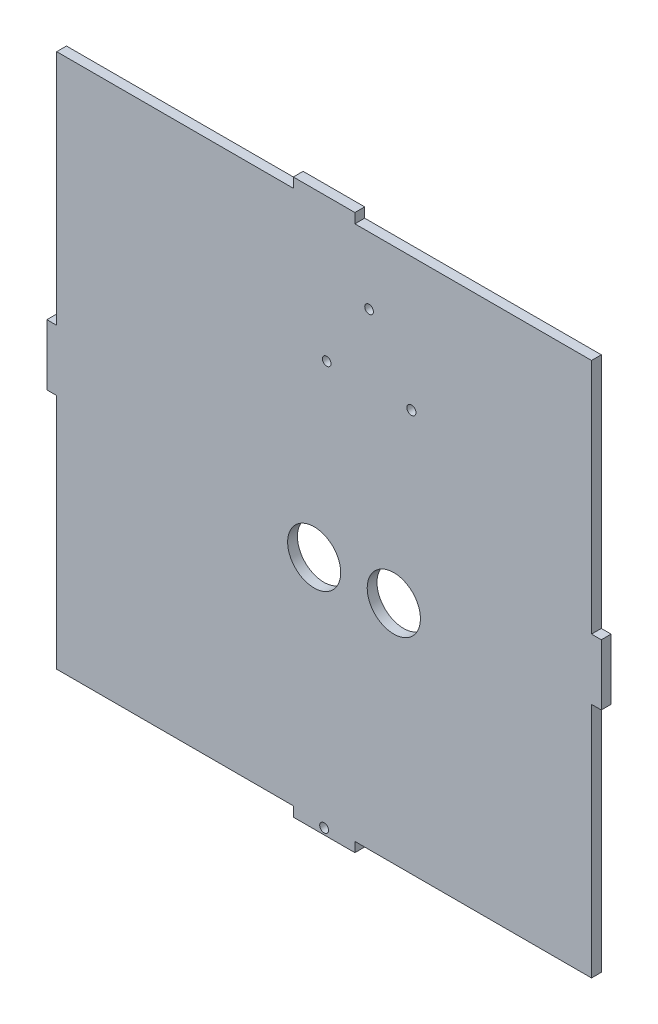
SolidWorks part; units mm, degrees
ref_plane "Front Plane" through (0, 0, 0) normal (0, 0, 1) x (1, 0, 0)
ref_plane "Top Plane" through (0, 0, 0) normal (0, 1, 0) x (1, 0, 0)
ref_plane "Right Plane" through (0, 0, 0) normal (1, 0, 0) x (0, 0, -1)
sketch "Sketch3" plane through (0, 0, 0) normal (0, 0, 1) x (1, 0, 0)
  line L0 (-90, 0) -> (90, 0) construction
  line L1 (-90, 90) -> (90, 90)
  line L2 (-90, 90) -> (-90, -90)
  line L3 (-90, -90) -> (90, -90)
  line L4 (90, 90) -> (90, -90)
  line L5 (-90, 0) -> (42.6717, 0) construction
  line L6 (0, 90) -> (0, -90) construction
  circle A0 centre (-3.2289, -13.5756) radius 8.617
  circle A1 centre (22.6311, -13.5756) radius 8.6439
  circle A2 centre (0, -88) radius 1.436
  circle A3 centre (0.8449, 43.6061) radius 1.4
  circle A4 centre (14.5949, 65.1061) radius 1.4
  circle A5 centre (28.3449, 43.6061) radius 1.4672
  dimension "D2" = 2.872
  dimension "D1" = 180
  dimension "D3" = 180
  dimension "D4" = 2
extrude "Boss-Extrude1" add sketch "Sketch3" along normal blind 3.18
sketch "Sketch4" plane through (0, 0, 3.18) normal (0, 0, 1) x (1, 0, 0)
  line L0 (-90, 90) -> (-90, -90) construction
  line L1 (90, -90) -> (90, 90) construction
  line L2 (-90, 0) -> (90, 0) construction
  line L3 (90, -86.82) -> (10, -86.82)
  line L4 (90, 90) -> (-90, 90) construction
  line L5 (0, -90) -> (0, 90) construction
  line L6 (-10, 86.82) -> (-90, 86.82)
  line L7 (-90, 86.82) -> (-90, 90)
  line L8 (-10, 90) -> (-10, 86.82)
  line L9 (-90, 90) -> (-10, 90)
  line L10 (10, 90) -> (10, 86.82)
  line L11 (10, 90) -> (90, 90)
  line L12 (90, 90) -> (90, 86.82)
  line L13 (90, 86.82) -> (10, 86.82)
  line L14 (90, -90) -> (90, -86.82)
  line L15 (10, -90) -> (90, -90)
  line L16 (10, -90) -> (10, -86.82)
  line L17 (-90, -90) -> (-10, -90)
  line L18 (-10, -90) -> (-10, -86.82)
  line L19 (-90, -90) -> (90, -90) construction
  line L20 (-90, -86.82) -> (-90, -90)
  line L21 (-10, -86.82) -> (-90, -86.82)
  dimension "D1" = 20
  dimension "D2" = 3.18
sketch "Sketch5" plane through (0, 0, 3.18) normal (0, 0, 1) x (1, 0, 0)
  line L0 (-90, 0) -> (90, 0) construction
  line L1 (-90, 90) -> (-86.82, 90)
  line L2 (-90, 90) -> (-90, 9.875)
  line L3 (-90, 9.875) -> (-86.82, 9.875)
  line L4 (-86.82, 90) -> (-86.82, 9.875)
  line L5 (-90, -90) -> (-86.82, -90)
  line L6 (-90, -90) -> (-90, -9.875)
  line L7 (-90, -9.875) -> (-86.82, -9.875)
  line L8 (-86.82, -90) -> (-86.82, -9.875)
  line L10 (0, 90) -> (0, -90) construction
  line L11 (86.82, -90) -> (86.82, -9.875)
  line L12 (90, -9.875) -> (86.82, -9.875)
  line L13 (90, -90) -> (90, -9.875)
  line L14 (90, -90) -> (86.82, -90)
  line L15 (86.82, 90) -> (86.82, 9.875)
  line L16 (90, 9.875) -> (86.82, 9.875)
  line L17 (90, 90) -> (90, 9.875)
  line L18 (90, 90) -> (86.82, 90)
  dimension "D1" = 3.18
  dimension "D2" = 3.18
  dimension "D3" = 19.75
extrude "Cut-Extrude1" cut sketch "Sketch4" against normal through all
extrude "Cut-Extrude2" cut sketch "Sketch5" against normal through all
